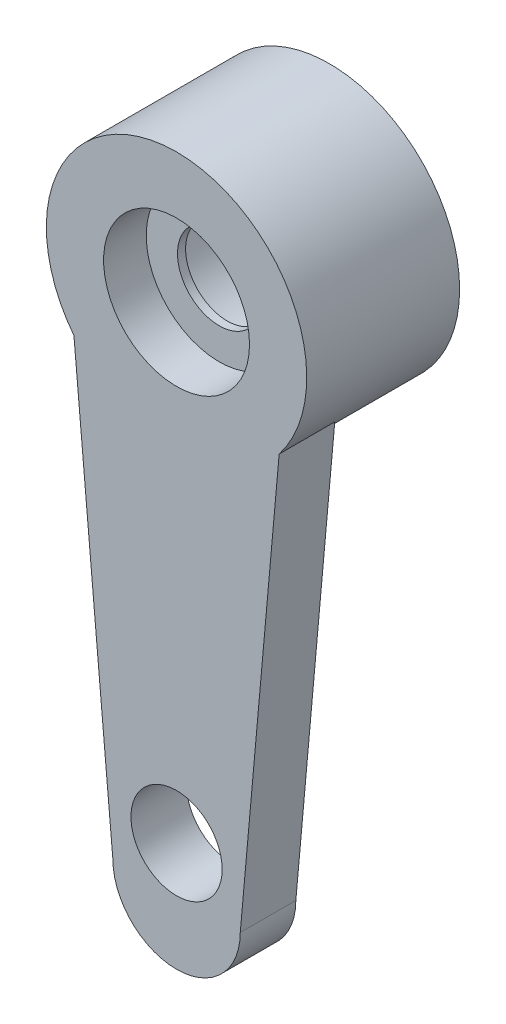
SolidWorks part; units mm, degrees
material "Nylon 6/10"
ref_plane "Front Plane" through (0, 0, 0) normal (0, 0, 1) x (1, 0, 0)
ref_plane "Top Plane" through (0, 0, 0) normal (0, 1, 0) x (1, 0, 0)
ref_plane "Right Plane" through (0, 0, 0) normal (1, 0, 0) x (0, 0, -1)
ref_plane "Plane1" through (0, 0, -7.033) normal (0, 0, 1) x (1, 0, 0)
sketch "Sketch1" plane through (0, 0, -7.033) normal (0, 0, 1) x (1, 0, 0)
  circle A0 centre (-5.5, 0) radius 3.5687
  circle A1 centre (-5.5, 0) radius 2
  dimension "D1" = 7.1374
extrude "Boss-Extrude1" add sketch "Sketch1" along normal blind 4.191
sketch "Sketch5" plane through (0, 0, -4.233) normal (0, 0, 1) x (1, 0, 0)
  circle A0 centre (-5.5, 0) radius 1.143
  circle A1 centre (-5.5, 0) radius 2 construction
  circle A2 centre (-5.5, 0) radius 2
  dimension "D1" = 2.286
extrude "Boss-Extrude2" add sketch "Sketch5" along normal offset from surface (0.2226 mm away) 1.1684 up to face at (-1.9313, 0, -2.842)
sketch "Sketch6" plane through (0, 0, -2.842) normal (0, 0, 1) x (1, 0, 0)
  line L0 (-3.7537, -14.0907) -> (-2.6869, -2.196)
  line L1 (-7.2462, -14.0907) -> (-8.313, -2.196)
  line L2 (-5.5, 0) -> (-5.5, -14.0907) construction
  arc A0 (-7.2462, -14.0907) -> (-3.7537, -14.0907) centre (-5.5, -14.0907) ccw
  circle A1 centre (-5.5, 0) radius 3.5687 construction
  circle A2 centre (-5.5, 0) radius 3.5687 construction
  circle A4 centre (-5.5, -12.8407) radius 1.25
  arc A9 (-2.6869, -2.196) -> (-8.313, -2.196) centre (-5.5, 0) cw
  point P11 (-5.5, -14.7157)
  point P12 (-5.5, -13.544)
  point P13 (-5.5, -13.7056)
  dimension "D1" = 3.4925
  dimension "D2" = 15.8369
  dimension "D3" = 5.6261
extrude "Boss-Extrude3" add sketch "Sketch6" against normal blind 1.524
